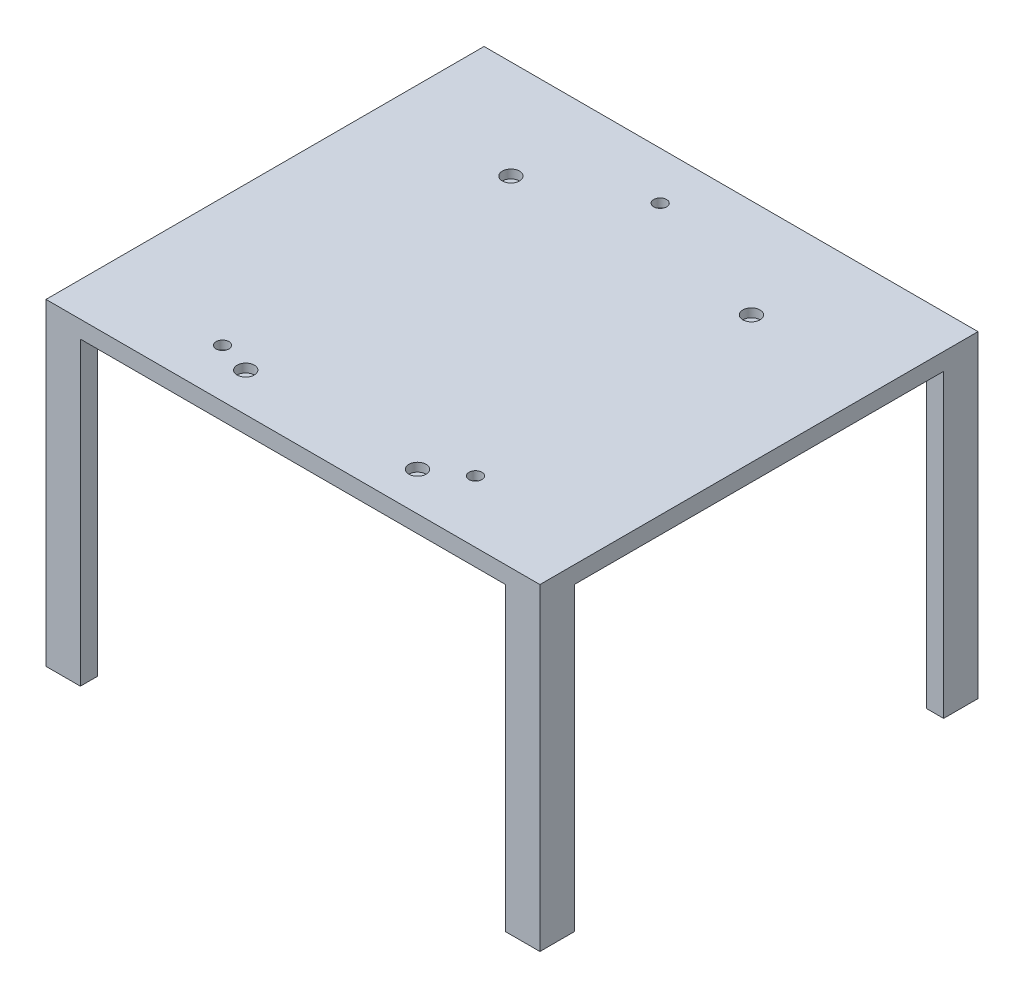
SolidWorks part; units mm, degrees
ref_plane "Front Plane" through (0, 0, 0) normal (0, 0, 1) x (1, 0, 0)
ref_plane "Top Plane" through (0, 0, 0) normal (0, 1, 0) x (1, 0, 0)
ref_plane "Right Plane" through (0, 0, 0) normal (1, 0, 0) x (0, 0, -1)
sketch "Sketch1" plane through (0, 0, 0) normal (0, 1, 0) x (1, 0, 0)
  line L1 (0, 0) -> (115, 0)
  line L2 (0, 0) -> (0, 102)
  line L3 (0, 102) -> (115, 102)
  line L4 (115, 0) -> (115, 102)
  dimension "D1" = 115
  dimension "D2" = 102
extrude "Boss-Extrude1" add sketch "Sketch1" along normal blind 4
sketch "Sketch3" plane through (0, 0, 0) normal (0, -1, 0) x (1, 0, 0)
  line L0 (115, -102) -> (0, -102) construction
  line L1 (5.5, -6) -> (20.5, -6)
  line L2 (5.5, -6) -> (5.5, -96)
  line L3 (5.5, -96) -> (20.5, -96)
  line L4 (20.5, -6) -> (20.5, -96)
  line L5 (57.5, 0) -> (57.5, -102) construction
  line L6 (0, 0) -> (115, 0) construction
  line L7 (0, -51) -> (115, -51) construction
  line L8 (109.5, -6) -> (94.5, -6)
  line L9 (109.5, -6) -> (109.5, -96)
  line L10 (109.5, -96) -> (94.5, -96)
  line L11 (94.5, -6) -> (94.5, -96)
  line L14 (0, -102) -> (0, 0) construction
  line L17 (115, 0) -> (115, -102) construction
  dimension "D1" = 104
  dimension "D2" = 90
  dimension "D3" = 15
  dimension "D4" = 90
extrude "Boss-Extrude2" add sketch "Sketch3" along normal blind 40
sketch "Sketch4" plane through (0, -40, 0) normal (0, -1, 0) x (1, 0, 0)
  line L0 (14.525, -69.75) -> (14.525, -64.5) construction
  line L3 (11.7, -69.75) -> (11.7, -64.5) construction
  line L6 (57.5, -102) -> (57.5, 0) construction
  line L7 (115, -102) -> (0, -102) construction
  line L8 (0, 0) -> (115, 0) construction
  line L9 (17.35, -69.75) -> (17.35, -64.5) construction
  line L10 (100.475, -69.75) -> (100.475, -64.5) construction
  line L11 (97.65, -69.75) -> (97.65, -64.5) construction
  line L12 (103.3, -69.75) -> (103.3, -64.5) construction
  line L13 (115, -51) -> (0, -51) construction
  line L14 (115, 0) -> (115, -102) construction
  line L15 (0, -102) -> (0, 0) construction
  line L16 (100.475, -32.25) -> (100.475, -37.5) construction
  line L17 (97.65, -32.25) -> (97.65, -37.5) construction
  line L18 (103.3, -32.25) -> (103.3, -37.5) construction
  line L19 (14.525, -32.25) -> (14.525, -37.5) construction
  line L20 (11.7, -32.25) -> (11.7, -37.5) construction
  line L21 (17.35, -32.25) -> (17.35, -37.5) construction
  arc A4 (11.7, -69.75) -> (17.35, -69.75) centre (14.525, -69.75) ccw construction
  arc A5 (17.35, -64.5) -> (11.7, -64.5) centre (14.525, -64.5) ccw construction
  arc A6 (97.65, -69.75) -> (103.3, -69.75) centre (100.475, -69.75) ccw construction
  arc A7 (103.3, -64.5) -> (97.65, -64.5) centre (100.475, -64.5) ccw construction
  arc A8 (97.65, -32.25) -> (103.3, -32.25) centre (100.475, -32.25) cw construction
  arc A9 (103.3, -37.5) -> (97.65, -37.5) centre (100.475, -37.5) cw construction
  arc A10 (11.7, -32.25) -> (17.35, -32.25) centre (14.525, -32.25) cw construction
  arc A11 (17.35, -37.5) -> (11.7, -37.5) centre (14.525, -37.5) cw construction
  circle A12 centre (14.525, -67.125) radius 2.125
  circle A13 centre (14.525, -34.875) radius 2.125
  circle A14 centre (100.475, -67.125) radius 2.125
  circle A15 centre (100.475, -34.875) radius 2.125
  point P2 (14.525, -67.125)
  point P7 (100.475, -67.125)
  point P22 (100.475, -34.875)
  point P23 (14.525, -72.575)
  point P24 (14.525, -61.675)
  point P37 (14.525, -34.875)
  point P42 (14.525, -40.325)
  dimension "D1" = 80.3
  dimension "D2" = 5.65
  dimension "D5" = 4.25
  dimension "D3" = 10.9
  dimension "D4" = 21.35
extrude "Cut-Extrude4" cut sketch "Sketch4" against normal blind 10
sketch "Sketch11" plane through (0, 4, 0) normal (0, 1, 0) x (1, 0, 0)
  line L5 (5.5, 96.5) -> (109.5, 96.5)
  line L6 (5.5, 96.5) -> (5.5, 5.5)
  line L7 (5.5, 5.5) -> (109.5, 5.5)
  line L8 (109.5, 96.5) -> (109.5, 5.5)
  line L10 (115, 102) -> (0, 102) construction
  line L11 (115, 0) -> (115, 102) construction
  point P6 (57.5, 102)
  point P7 (57.5, 96.5)
  point P10 (115, 51)
  point P11 (109.5, 51)
  dimension "D1" = 104
  dimension "D2" = 91
extrude "Cut-Extrude5" cut sketch "Sketch11" against normal blind 2
sketch "Sketch14" plane through (0, 0, 0) normal (0, -1, 0) x (1, 0, 0)
  line L2 (115, -102) -> (0, -102) construction
  line L3 (115, 0) -> (115, -102) construction
  line L4 (57.5, -102) -> (57.5, 0) construction
  line L5 (115, -51) -> (0, -51) construction
  line L6 (57.5, -102) -> (57.5, 0) construction
  line L7 (115, -51) -> (0, -51) construction
  circle A0 centre (109, -100) radius 1
  circle A1 centre (113, -96) radius 1
  circle A2 centre (2, -96) radius 1
  circle A3 centre (6, -100) radius 1
  circle A4 centre (113, -6) radius 1
  circle A5 centre (109, -2) radius 1
  circle A6 centre (2, -6) radius 1
  circle A7 centre (6, -2) radius 1
  dimension "D3" = 2
  dimension "D4" = 2
  dimension "D1" = 2
  dimension "D2" = 6
  dimension "D5" = 6
extrude "Cut-Extrude7" cut sketch "Sketch14" against normal blind 20
sketch "Sketch6" plane through (0, 4, 0) normal (0, 1, 0) x (1, 0, 0)
  line L0 (0, 0) -> (0, 8)
  line L1 (0, 102) -> (0, 0) construction
  line L2 (0, 8) -> (4, 8)
  line L3 (4, 8) -> (4, 4)
  line L4 (4, 4) -> (8, 4)
  line L5 (8, 4) -> (8, 0)
  line L6 (0, 0) -> (115, 0) construction
  line L7 (8, 0) -> (0, 0)
  line L8 (57.5, 0) -> (57.5, 102) construction
  line L9 (115, 102) -> (0, 102) construction
  line L10 (0, 51) -> (115, 51) construction
  line L11 (115, 0) -> (115, 102) construction
  line L12 (107, 0) -> (115, 0)
  line L13 (107, 4) -> (107, 0)
  line L14 (111, 4) -> (107, 4)
  line L15 (111, 8) -> (111, 4)
  line L16 (115, 8) -> (111, 8)
  line L17 (115, 0) -> (115, 8)
  line L18 (107, 102) -> (115, 102)
  line L19 (115, 102) -> (115, 94)
  line L20 (115, 94) -> (111, 94)
  line L21 (111, 94) -> (111, 98)
  line L22 (111, 98) -> (107, 98)
  line L23 (107, 98) -> (107, 102)
  line L24 (8, 102) -> (0, 102)
  line L25 (8, 98) -> (8, 102)
  line L26 (4, 98) -> (8, 98)
  line L27 (4, 94) -> (4, 98)
  line L28 (0, 94) -> (4, 94)
  line L29 (0, 102) -> (0, 94)
  dimension "D1" = 4
  dimension "D2" = 4
  dimension "D3" = 8
  dimension "D4" = 8
extrude "Boss-Extrude4" add sketch "Sketch6" along normal blind 70
sketch "Sketch13" plane through (0, 0, 0) normal (0, -1, 0) x (1, 0, 0)
  line L1 (107, -98) -> (107, -102) construction
  line L2 (111, -98) -> (107, -98) construction
  line L4 (111, -94) -> (111, -98) construction
  line L5 (115, -94) -> (111, -94) construction
  line L6 (57.5, 0) -> (57.5, -102) construction
  line L7 (0, -51) -> (115, -51) construction
  line L8 (57.5, 0) -> (57.5, -102) construction
  line L9 (0, -51) -> (115, -51) construction
  circle A0 centre (109, -100) radius 1
  circle A1 centre (113, -96) radius 1
  circle A2 centre (2, -96) radius 1
  circle A3 centre (6, -100) radius 1
  circle A4 centre (113, -6) radius 1
  circle A5 centre (109, -2) radius 1
  circle A6 centre (6, -2) radius 1
  circle A7 centre (2, -6) radius 1
  dimension "D1" = 2
  dimension "D4" = 2
  dimension "D2" = 2
  dimension "D3" = 2
  dimension "D5" = 2
  dimension "D6" = 2
extrude "Cut-Extrude6" cut sketch "Sketch13" against normal blind 20
sketch "Sketch7" plane through (0, 74, 0) normal (0, 1, 0) x (1, 0, 0)
  line L1 (0, 0) -> (115, 0)
  line L2 (0, 0) -> (0, 102)
  line L3 (0, 102) -> (115, 102)
  line L4 (115, 0) -> (115, 102)
extrude "Boss-Extrude5" add sketch "Sketch7" along normal blind 4
sketch "Sketch8" plane through (0, 78, 0) normal (0, 1, 0) x (1, 0, 0)
  line L0 (0, 51) -> (115, 51) construction
  line L1 (0, 102) -> (0, 0) construction
  line L2 (115, 0) -> (115, 102) construction
  line L3 (57.5, 102) -> (57.5, 0) construction
  line L4 (115, 102) -> (0, 102) construction
  line L5 (0, 0) -> (115, 0) construction
  circle A0 centre (29.25, 79) radius 2
  circle A1 centre (85.25, 79) radius 2
  circle A2 centre (37.5, 9) radius 2
  circle A3 centre (77.5, 9) radius 2
  dimension "D1" = 4
  dimension "D2" = 56
  dimension "D3" = 70
  dimension "D4" = 40
  dimension "D5" = 28
  dimension "D6" = 20
  dimension "D7" = 28.25
extrude "Cut-Extrude2" cut sketch "Sketch8" against normal blind 2
sketch "Sketch9" plane through (0, 78, 0) normal (0, 1, 0) x (1, 0, 0)
  line L0 (0, 51) -> (115, 51) construction
  line L1 (0, 102) -> (0, 0) construction
  line L2 (115, 0) -> (115, 102) construction
  line L3 (57.5, 0) -> (57.5, 102) construction
  line L4 (0, 0) -> (115, 0) construction
  line L5 (115, 102) -> (0, 102) construction
  circle A0 centre (52.1, 90.9) radius 1.5
  circle A1 centre (85.6, 14.4) radius 1.5
  circle A2 centre (29.8, 11.3) radius 1.5
  dimension "D1" = 3
  dimension "D2" = 76.5
  dimension "D3" = 79.6
  dimension "D4" = 5.4
  dimension "D5" = 27.7
  dimension "D6" = 28.1
  dimension "D7" = 39.9
extrude "Cut-Extrude3" cut sketch "Sketch9" against normal blind 2
sketch "Sketch15" plane through (0, 4, 0) normal (0, 1, 0) x (1, 0, 0)
  line L1 (-13.0383, -12.5208) -> (155.1935, -12.5208)
  line L2 (-13.0383, -12.5208) -> (-13.0383, 117.0663)
  line L3 (-13.0383, 117.0663) -> (155.1935, 117.0663)
  line L4 (155.1935, -12.5208) -> (155.1935, 117.0663)
extrude "Cut-Extrude8" cut sketch "Sketch15" against normal through all
